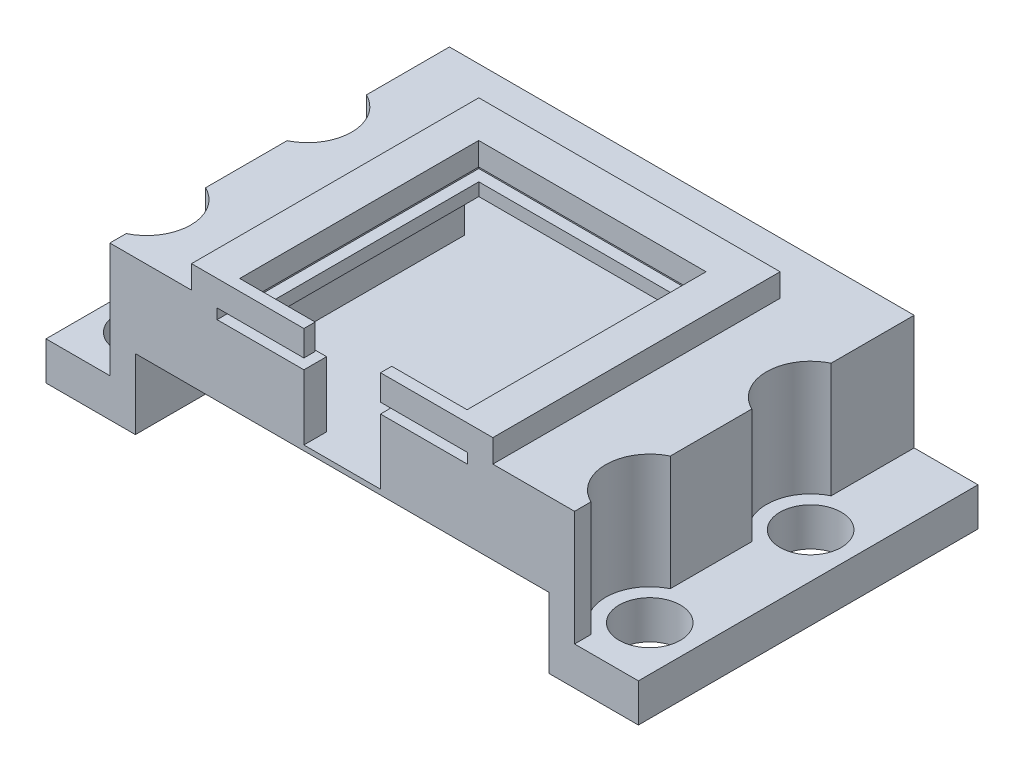
SolidWorks part; units mm, degrees
ref_plane "Front Plane" through (0, 0, 0) normal (0, 0, 1) x (1, 0, 0)
ref_plane "Top Plane" through (0, 0, 0) normal (0, 1, 0) x (1, 0, 0)
ref_plane "Right Plane" through (0, 0, 0) normal (1, 0, 0) x (0, 0, -1)
sketch "Sketch1" plane through (0, 0, 0) normal (0, 1, 0) x (1, 0, 0)
  line L0 (-11.0657, -8.7823) -> (-12.0657, -8.7823)
  line L1 (-11.0657, 3.5177) -> (5.1343, 3.5177)
  line L2 (-11.0657, 3.5177) -> (-11.0657, -8.7823)
  line L4 (5.1343, 3.5177) -> (5.1343, -8.7823)
  line L5 (-12.0657, -8.7823) -> (-12.0657, 4.5177)
  line L6 (-12.0657, 4.5177) -> (6.1343, 4.5177)
  line L7 (6.1343, 4.5177) -> (6.1343, -8.7823)
  line L8 (6.1343, -8.7823) -> (5.1343, -8.7823)
  dimension "D1" = 12.3
  dimension "D2" = 16.2
  dimension "D3" = 1
  dimension "D4" = 1
  dimension "D5" = 1
  dimension "D6" = 13.3
extrude "Boss-Extrude1" add sketch "Sketch1" along normal blind 5.5
sketch "Sketch2" plane through (0, 0, -4.5177) normal (0, 0, -1) x (-1, 0, 0)
  line L0 (2.9657, 0) -> (2.9657, 5.5) construction
  line L1 (-6.1343, 0) -> (12.0657, 0) construction
  line L2 (-6.1343, 5.5) -> (12.0657, 5.5) construction
  line L3 (-6.1343, 2.05) -> (12.0657, 2.05) construction
  line L4 (-6.1343, 5.5) -> (-6.1343, 0) construction
  line L5 (12.0657, 5.5) -> (12.0657, 0) construction
  line L7 (-5.1343, 5.5) -> (-5.1343, 0) construction
  line L8 (-5.1843, 0) -> (11.1157, 0) construction
  line L9 (11.0657, 5.5) -> (11.0657, 0) construction
  line L10 (11.1157, 5.5) -> (-5.1843, 5.5) construction
  line L12 (-5.1343, 2.05) -> (11.0657, 2.05)
  line L13 (-5.1343, 2.05) -> (-5.1343, 0.7)
  line L14 (-5.1343, 0.7) -> (11.0657, 0.7)
  line L15 (11.0657, 2.05) -> (11.0657, 0.7)
  dimension "D1" = 1
  dimension "D2" = 1
  dimension "D3" = 0
  dimension "D4" = 1.35
  dimension "D5" = 0
  dimension "D6" = 3.45
extrude "Cut-Extrude1" cut sketch "Sketch2" against normal blind 3
sketch "Sketch5" plane through (0, 5.5, 0) normal (0, 1, 0) x (1, 0, 0)
  line L0 (-11.0657, -8.7823) -> (5.1343, -8.7823) construction
  line L1 (-2.9657, 3.5177) -> (-2.9657, -8.7823) construction
  line L2 (-11.0657, 3.5177) -> (5.1343, 3.5177) construction
  line L3 (6.1343, 4.5177) -> (-12.0657, 4.5177) construction
  line L4 (-7.8657, 1.4677) -> (1.9343, 1.4677)
  line L5 (-7.8657, 1.4677) -> (-7.8657, -8.3423)
  line L6 (-7.8657, -8.3423) -> (1.9343, -8.3423)
  line L7 (1.9343, 1.4677) -> (1.9343, -8.3423)
  line L8 (-12.0657, 4.5177) -> (-12.0657, -8.7823) construction
  line L9 (6.1343, -8.7823) -> (6.1343, 4.5177) construction
  line L11 (-12.0657, 4.5177) -> (6.1343, 4.5177)
  line L12 (-12.0657, 4.5177) -> (-12.0657, -8.7823)
  line L13 (-12.0657, -8.7823) -> (6.1343, -8.7823)
  line L14 (6.1343, 4.5177) -> (6.1343, -8.7823)
  dimension "D1" = 3.05
  dimension "D2" = 0.44
  dimension "D3" = 4.2
  dimension "D4" = 4.2
extrude "Boss-Extrude2" add sketch "Sketch5" along normal blind 0.5
sketch "Sketch6" plane through (0, 5.5, 0) normal (0, -1, 0) x (1, 0, 0)
  line L0 (-11.0657, 8.7823) -> (5.1343, 8.7823) construction
  line L1 (-8.4596, 8.7823) -> (2.6477, 8.7823)
  line L2 (-8.4596, 8.7823) -> (-8.4596, -2.0777)
  line L3 (-8.4596, -2.0777) -> (2.6477, -2.0777)
  line L4 (2.6477, 8.7823) -> (2.6477, -2.0777)
  line L6 (-2.906, 8.7823) -> (-2.906, -2.0777) construction
  line L7 (-8.4596, 3.3523) -> (2.6477, 3.3523) construction
  line L8 (1.9343, -1.4677) -> (-7.8657, -1.4677) construction
  line L9 (-7.4157, 7.8923) -> (1.4843, 7.8923)
  line L10 (-7.4157, 7.8923) -> (-7.4157, -1.0177)
  line L11 (-7.4157, -1.0177) -> (1.4843, -1.0177)
  line L12 (1.4843, 7.8923) -> (1.4843, -1.0177)
  line L13 (-7.8657, -1.4677) -> (-7.8657, 8.3423) construction
  line L15 (1.9343, 8.3423) -> (1.9343, -1.4677) construction
  line L16 (-7.8657, 8.3423) -> (1.9343, 8.3423) construction
  dimension "D1" = 0.45
  dimension "D2" = 0.45
  dimension "D3" = 0.45
  dimension "D4" = 0.45
extrude "Boss-Extrude3" add sketch "Sketch6" along normal blind 0.5
sketch "Sketch7" plane through (0, 0, -3.5177) normal (0, 0, 1) x (1, 0, 0)
  line L0 (-11.0657, 5.5) -> (-11.0657, 0) construction
  line L1 (-11.0657, 2.75) -> (5.1343, 2.75)
  line L2 (-11.0657, 2.75) -> (-11.0657, 2.95)
  line L3 (-11.0657, 2.95) -> (5.1343, 2.95)
  line L4 (5.1343, 2.75) -> (5.1343, 2.95)
  line L5 (5.1343, 5.5) -> (5.1343, 2.05) construction
  line L6 (-11.0657, 2.05) -> (5.1343, 2.05) construction
  dimension "D1" = 0.9
extrude "Boss-Extrude4" add sketch "Sketch7" along normal blind 12.3
sketch "Sketch8" plane through (0, 0, 0) normal (0, -1, 0) x (-1, 0, 0)
  line L0 (11.0657, 3.5177) -> (-5.1343, 3.5177) construction
  line L2 (11.0657, -8.7823) -> (11.0657, 3.5177)
  line L4 (-5.1343, -8.7823) -> (-5.1343, 3.5177)
  line L5 (11.0657, 3.5177) -> (-5.1343, 3.5177) construction
  line L6 (14.5657, -8.7823) -> (14.5657, 4.5177)
  line L8 (-8.6343, -8.7823) -> (-8.6343, 4.5177)
  line L10 (12.0657, -8.7823) -> (14.5657, -8.7823)
  line L11 (-6.1343, -8.7823) -> (-8.6343, -8.7823)
  line L12 (12.0657, 4.5177) -> (14.5657, 4.5177)
  line L13 (-6.1343, 4.5177) -> (-8.6343, 4.5177)
  line L14 (12.0657, -8.7823) -> (11.0657, -8.7823)
  line L15 (14.5657, -12.2823) -> (14.5657, 7.0177) construction
  line L16 (14.5657, -12.2823) -> (-8.6343, -12.2823) construction
  line L17 (-8.6343, -12.2823) -> (-8.6343, 7.0177) construction
  line L18 (14.5657, 7.0177) -> (-8.6343, 7.0177) construction
  line L19 (-5.1343, -8.7823) -> (-6.1343, -8.7823)
  line L20 (-6.1343, 4.5177) -> (-5.1343, 4.5177)
  line L21 (-5.1343, 3.5177) -> (-5.1343, 4.5177)
  line L22 (11.0657, -8.7823) -> (-5.1343, -8.7823) construction
  line L23 (11.0657, 3.5177) -> (11.0657, 4.5177)
  line L24 (11.0657, 4.5177) -> (12.0657, 4.5177)
  line L25 (11.0657, 3.5177) -> (-5.1343, 3.5177) construction
  dimension "D1" = 3.5
extrude "Boss-Extrude5" add sketch "Sketch8" against normal blind 1.5
ref_plane "Plane1" through (0, 0, 3.4373) normal (0, 0, 1) x (1, 0, 0)
sketch "Sketch10" plane through (0, 0, 0) normal (0, -1, 0) x (-1, 0, 0)
  line L0 (14.5657, -8.7823) -> (14.5657, 4.5177) construction
  line L2 (-8.6343, 4.5177) -> (14.5657, 4.5177) construction
  line L3 (2.9657, 4.5177) -> (2.9657, -8.7823) construction
  line L4 (11.0657, -8.7823) -> (-5.1343, -8.7823) construction
  line L5 (-0.275, -3.4373) -> (0.275, -3.4373) construction
  circle A0 centre (12.8157, -6.5873) radius 1.2
  circle A1 centre (12.8157, -0.2873) radius 1.2
  circle A2 centre (-6.8843, -0.2873) radius 1.2
  circle A3 centre (-6.8843, -6.5873) radius 1.2
  dimension "D1" = 2.4
  dimension "D4" = 2.4
  dimension "D2" = 1.75
  dimension "D3" = 6.3
  dimension "D5" = 3.15
  dimension "D6" = 1.75
extrude "Cut-Extrude7" cut sketch "Sketch10" against normal through all both and the other way through all contours A1 | A0 | A2 | A3
sketch "Sketch11" plane through (0, 1.5, 0) normal (0, 1, 0) x (1, 0, 0)
  circle A0 centre (6.8843, -0.2873) radius 1.725
  circle A1 centre (6.8843, -6.5873) radius 1.725
  circle A2 centre (-12.8157, -0.2873) radius 1.725
  circle A3 centre (-12.8157, -6.5873) radius 1.725
  dimension "D1" = 3.45
  dimension "D2" = 3.45
  dimension "D3" = 3.45
  dimension "D4" = 3.45
extrude "Cut-Extrude11" cut sketch "Sketch11" along normal blind 10 contours A3 | A2 | A0 | A1
ref_plane "Plane4" through (0, 0, -1.4677) normal (0, 0, 1) x (1, 0, 0)
ref_plane "Plane5" through (0, 5.5, 0) normal (0, 1, 0) x (1, 0, 0)
sketch "Sketch17" plane through (0, 0, 8.7823) normal (0, 0, 1) x (1, 0, 0)
  line L0 (5.39, 5.5) -> (-5.39, 5.5) construction
  line L1 (-7.8657, 5.5) -> (1.9343, 5.5)
  line L2 (-7.8657, 5.5) -> (-7.8657, 5.9)
  line L3 (-7.8657, 5.9) -> (1.9343, 5.9)
  line L4 (1.9343, 5.5) -> (1.9343, 5.9)
  line L5 (1.9343, 6) -> (1.9343, 5.5) construction
  line L6 (-7.8657, 6) -> (-7.8657, 5.5) construction
  dimension "D1" = 0.4
  dimension "D2" = 0
  dimension "D3" = 0
extrude "Cut-Extrude12" cut sketch "Sketch17" against normal up to surface (10.25 mm away) up to plane "Plane4"
sketch "Sketch18" plane through (0, 6, 0) normal (0, 1, 0) x (1, 0, 0)
  line L0 (-12.0657, -8.7823) -> (6.1343, -8.7823) construction
  line L1 (-7.4199, -8.7823) -> (-8.8657, -8.7823)
  line L2 (-7.4199, -8.7823) -> (-7.4199, 1.0177)
  line L3 (-7.4199, 2.4677) -> (-8.8657, 2.4677)
  line L4 (-8.8657, -8.7823) -> (-8.8657, 2.4677)
  line L5 (-0.275, 1.4677) -> (0.275, 1.4677) construction
  line L6 (1.4843, -8.7823) -> (2.9343, -8.7823)
  line L7 (1.4843, -8.7823) -> (1.4843, 1.0177)
  line L8 (1.4843, 2.4677) -> (2.9343, 2.4677)
  line L9 (2.9343, -8.7823) -> (2.9343, 2.4677)
  line L10 (1.9343, -8.7823) -> (1.9343, 1.4677) construction
  line L11 (-7.8657, 1.4677) -> (-7.8657, -8.3423) construction
  line L13 (-7.4199, 2.4677) -> (1.4843, 2.4677)
  line L15 (-7.4199, 1.0177) -> (1.4843, 1.0177)
  dimension "D1" = 1
  dimension "D2" = 1
  dimension "D3" = 1
  dimension "D4" = 1
extrude "Boss-Extrude7" add sketch "Sketch18" along normal blind 1.5
sketch "Sketch19" plane through (0, 6, 0) normal (0, 1, 0) x (1, 0, 0)
  line L1 (-7.4199, -8.3423) -> (1.4843, -8.3423)
  line L2 (-7.4199, -8.3423) -> (-7.4199, -8.7823)
  line L3 (-7.4199, -8.7823) -> (1.4843, -8.7823)
  line L4 (1.4843, -8.3423) -> (1.4843, -8.7823)
extrude "Boss-Extrude8" add sketch "Sketch19" along normal offset from surface (0.9 mm away) 1 up to face at (-2.9657, 5.9, 8.5623)
ref_plane "Plane7" through (-2.9657, 0, 0) normal (1, 0, 0) x (0, 0, -1)
sketch "Sketch21" plane through (-2.9657, 0, 0) normal (1, 0, 0) x (0, 0, -1)
  line L1 (-8.7823, 6.9) -> (-7.8923, 6.9)
  line L2 (-8.7823, 6.9) -> (-8.7823, 5)
  line L3 (-8.7823, 5) -> (-7.8923, 5)
  line L4 (-7.8923, 6.9) -> (-7.8923, 5)
extrude "Cut-Extrude13" cut sketch "Sketch21" against normal blind 1.5 and the other way blind 1.5
sketch "Sketch22" plane through (0, 0, 8.7823) normal (0, 0, 1) x (1, 0, 0)
  line L0 (5.1343, 2.95) -> (-11.0657, 2.95) construction
  line L1 (-11.0657, 5.5) -> (-8.4339, 5.5)
  line L2 (-11.0657, 5.5) -> (-11.0657, 2.95)
  line L3 (-11.0657, 2.95) -> (-8.4339, 2.95)
  line L4 (-8.4339, 5.5) -> (-8.4339, 2.95)
  line L6 (2.6477, 5.5) -> (5.1343, 5.5)
  line L7 (2.6477, 5.5) -> (2.6477, 2.95)
  line L8 (2.6477, 2.95) -> (5.1343, 2.95)
  line L9 (5.1343, 5.5) -> (5.1343, 2.95)
extrude "Boss-Extrude9" add sketch "Sketch22" against normal up to surface (10.25 mm away)
sketch "Sketch23" plane through (0, 5, 0) normal (0, 1, 0) x (1, 0, 0)
  line L0 (-4.4657, -7.8923) -> (-4.4657, -8.7823)
  line L5 (-8.4339, 1.4677) -> (-8.4339, -8.7823) construction
  line L7 (2.6477, -8.7823) -> (-1.4657, -8.7823)
  line L8 (2.6477, -8.7823) -> (2.6477, -7.8923)
  line L9 (2.6477, -7.8923) -> (-1.4657, -7.8923)
  line L10 (-8.4339, -8.7823) -> (-8.4339, -7.8923)
  line L11 (-4.4657, -7.8923) -> (-7.4157, -7.8923) construction
  line L12 (-1.4657, -7.8923) -> (-1.4657, -8.7823)
  line L13 (-4.4657, -8.7823) -> (-8.4339, -8.7823)
  line L14 (-4.4657, -7.8923) -> (-8.4339, -7.8923)
  dimension "D1" = 0
  dimension "D2" = 0
extrude "Boss-Extrude11" add sketch "Sketch23" against normal up to surface (2.05 mm away) contours L14 L10 L13 L0 | L7 L12 L9 L8 up to face at (-2.9294, 2.95, 0.5823)
sketch "Sketch24" plane through (0, 7.5, 0) normal (0, 1, 0) x (1, 0, 0)
  line L0 (2.9343, 2.4677) -> (-8.8657, 2.4677) construction
  line L1 (-8.8657, -8.7823) -> (-7.4199, -8.7823)
  line L2 (-8.8657, -8.7823) -> (-8.8657, 2.4677)
  line L3 (-8.8657, 2.4677) -> (-7.5001, 2.4677)
  line L4 (-7.4199, -8.7823) -> (-7.4199, 1.0177)
  line L5 (2.9343, -8.7823) -> (2.9343, 2.4677) construction
  line L6 (-8.8657, 2.4677) -> (2.9343, 2.4677)
  line L7 (-8.8657, 2.4677) -> (-8.8657, 1.0177)
  line L8 (-7.4199, 1.0177) -> (1.4843, 1.0177)
  line L9 (2.9343, 2.4677) -> (2.9343, 1.0177)
  line L10 (-7.4199, -8.7823) -> (-7.4199, 1.0177) construction
  line L11 (2.9343, 2.4677) -> (1.4843, 2.4677)
  line L12 (2.9343, 2.4677) -> (2.9343, -8.7823)
  line L13 (2.9343, -8.7823) -> (1.4843, -8.7823)
  line L14 (1.4843, 1.0177) -> (1.4843, -8.7823)
  line M9 (-7.4199, -8.7823) -> (-7.4199, 1.0177)
  line M10 (-7.4199, 1.0177) -> (1.4843, 1.0177)
  line M11 (1.4843, 1.0177) -> (1.4843, -8.7823)
  line M12 (1.4843, -8.7823) -> (2.9343, -8.7823)
  line M13 (2.9343, -8.7823) -> (2.9343, 2.4677)
  line M14 (2.9343, 2.4677) -> (-8.8657, 2.4677)
  line M15 (-8.8657, 2.4677) -> (-8.8657, -8.7823)
  line M16 (-8.8657, -8.7823) -> (-7.4199, -8.7823)
  dimension "D1" = 0
extrude "Cut-Extrude14" cut sketch "Sketch24" against normal up to surface (0.6 mm away) contours L6 L2 M16 M9 M10 M11 M12 M13 M14 M15 up to face at (0.0093, 6.9, 8.5623)
